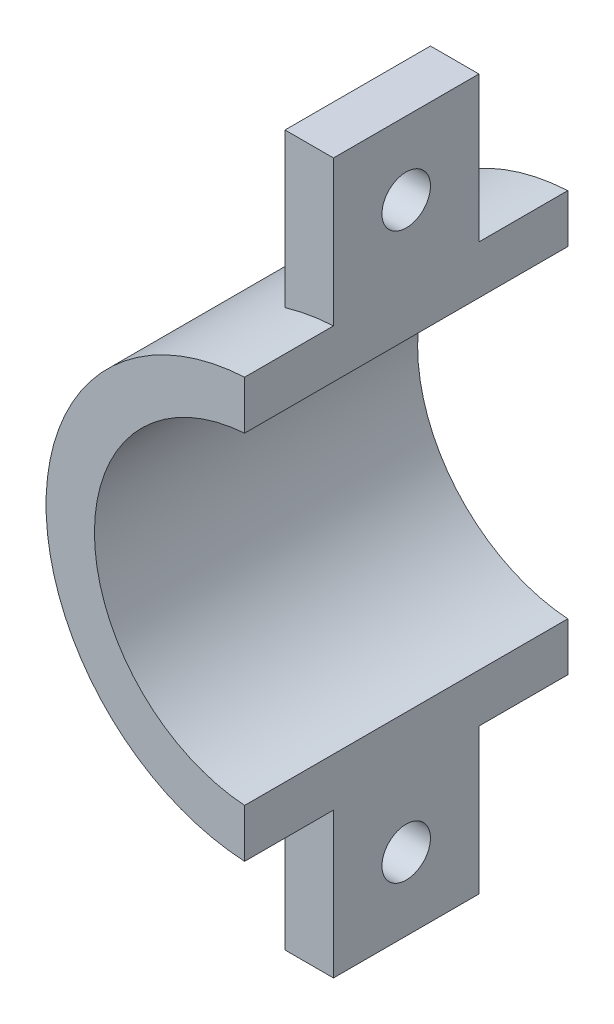
SolidWorks part; units mm, degrees
ref_plane "Спереди" through (0, 0, 0) normal (0, 0, 1) x (1, 0, 0)
ref_plane "Сверху" through (0, 0, 0) normal (0, 1, 0) x (1, 0, 0)
ref_plane "Справа" through (0, 0, 0) normal (1, 0, 0) x (0, 0, -1)
sketch "Эскиз1" plane through (0, 0, 0) normal (0, 0, 1) x (1, 0, 0)
  line L0 (-0.7067, 9.975) -> (-0.7067, 12.975)
  line L1 (-0.7067, -9.975) -> (-0.7067, -12.975)
  arc A0 (-0.7067, 9.975) -> (-0.7067, -9.975) centre (0, 0) ccw
  arc A1 (-0.7067, 12.975) -> (-0.7067, -12.975) centre (0, 0) ccw
  dimension "D1" = 10
  dimension "D3" = 19.95
  dimension "D2" = 3
extrude "Бобышка-Вытянуть1" add sketch "Эскиз1" along normal blind 20
sketch "Эскиз2" plane through (-0.7067, 0, 0) normal (1, 0, 0) x (0, 0, -1)
sketch "Эскиз3" plane through (-0.7067, 0, 0) normal (1, 0, 0) x (0, 0, -1)
  line L0 (-10, 9.975) -> (-10, -9.975) construction
  line L1 (-20, 9.975) -> (0, 9.975) construction
  line L2 (-20, -9.975) -> (0, -9.975) construction
  line L3 (-10, 9.975) -> (-14.5, 9.975)
  line L4 (-14.5, 9.975) -> (-14.5, 21.975)
  line L5 (-14.5, 21.975) -> (-5.5, 21.975)
  line L6 (-5.5, 21.975) -> (-5.5, 9.975)
  line L7 (-5.5, 9.975) -> (-10, 9.975)
  line L9 (-10, -9.975) -> (-14.5, -9.975)
  line L10 (-14.5, -9.975) -> (-14.5, -21.975)
  line L11 (-14.5, -21.975) -> (-5.5, -21.975)
  line L12 (-5.5, -21.975) -> (-5.5, -9.975)
  line L13 (-5.5, -9.975) -> (-10, -9.975)
  circle A0 centre (-10, 17.475) radius 1.5
  circle A1 centre (-10, -17.475) radius 1.5
  dimension "D1" = 3
  dimension "D2" = 4.5
  dimension "D3" = 7.5
  dimension "D4" = 12
  dimension "D5" = 4.5
  dimension "D6" = 7.5
  dimension "D7" = 4.5
extrude "Бобышка-Вытянуть2" add sketch "Эскиз3" against normal blind 3
